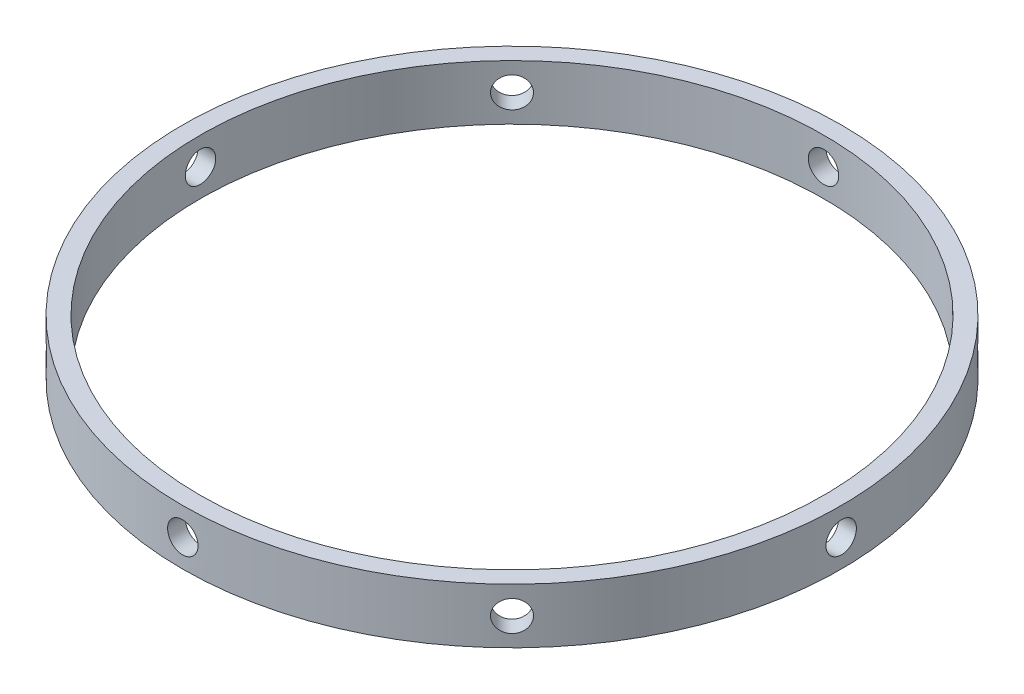
SolidWorks part; units mm, degrees
ref_plane "Front Plane" through (0, 0, 0) normal (0, 0, 1) x (1, 0, 0)
ref_plane "Top Plane" through (0, 0, 0) normal (0, 1, 0) x (1, 0, 0)
ref_plane "Right Plane" through (0, 0, 0) normal (1, 0, 0) x (0, 0, -1)
sketch "Sketch2" plane through (0, 0, 0) normal (0, 1, 0) x (1, 0, 0)
  circle A1 centre (-232.0876, -128.6295) radius 35.941
  circle A2 centre (-232.0876, -128.6295) radius 37.973
extrude "Boss-Extrude1" add sketch "Sketch2" along normal blind 6.35
sketch "Sketch3" plane through (0, 0, 0) normal (1, 0, 0) x (0, 0, -1)
  circle A1 centre (-128.6295, 3.175) radius 1.7526
extrude "Cut-Extrude1" cut sketch "Sketch3" against normal blind 200.35
pattern_circular "CirPattern1" count 8 over 360 of "Cut-Extrude1"
